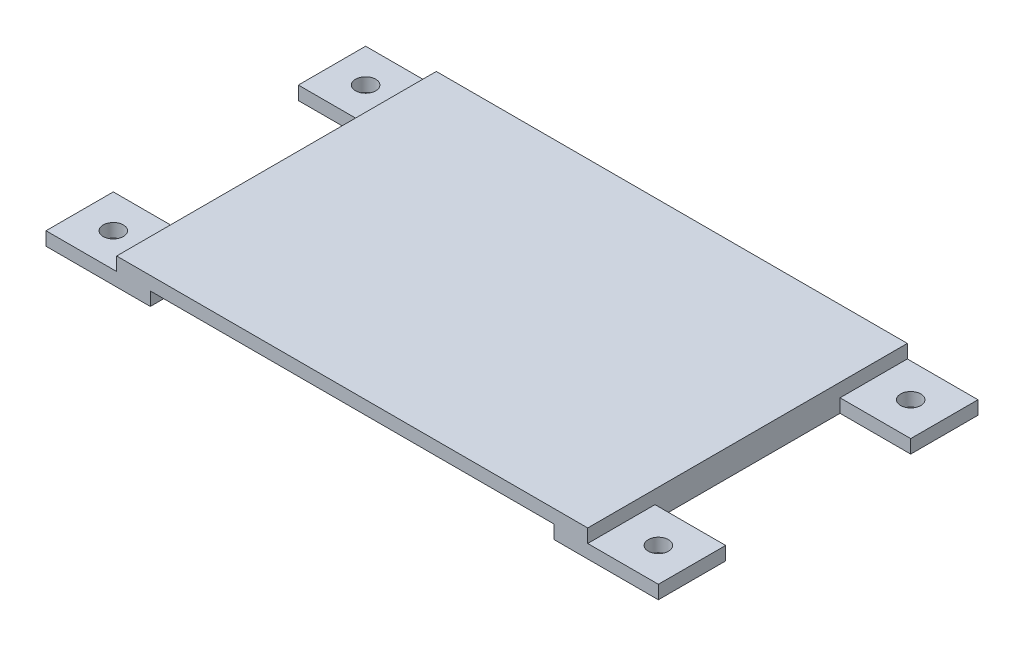
SolidWorks part; units mm, degrees
ref_plane "Front Plane" through (0, 0, 0) normal (0, 0, 1) x (1, 0, 0)
ref_plane "Top Plane" through (0, 0, 0) normal (0, 1, 0) x (1, 0, 0)
ref_plane "Right Plane" through (0, 0, 0) normal (1, 0, 0) x (0, 0, -1)
sketch "Sketch1" plane through (0, 0, 0) normal (0, 1, 0) x (1, 0, 0)
  line L0 (0, 0) -> (21, 0)
  line L1 (21, 0) -> (161, 0)
  line L8 (182, -95) -> (0, -95)
  line L9 (0, -95) -> (0, -75)
  line L10 (0, -75) -> (21, -75)
  line L11 (21, -75) -> (21, -20)
  line L12 (21, -20) -> (0, -20)
  line L13 (0, -20) -> (0, 0)
  line L14 (91, 0) -> (91, -95) construction
  line L15 (182, 0) -> (161, 0)
  line L16 (182, -20) -> (182, 0)
  line L17 (161, -20) -> (182, -20)
  line L18 (161, -75) -> (161, -20)
  line L19 (182, -75) -> (161, -75)
  line L20 (182, -95) -> (182, -75)
  circle A0 centre (10, -10) radius 3
  circle A1 centre (10, -85) radius 3
  circle A2 centre (172, -10) radius 3
  circle A3 centre (172, -85) radius 3
  dimension "D3" = 6
  dimension "D4" = 10
  dimension "D5" = 10
  dimension "D7" = 75
  dimension "D9" = 6
  dimension "D10" = 10
  dimension "D12" = 10
  dimension "D1" = 20
  dimension "D2" = 55
  dimension "D6" = 21
  dimension "D8" = 20
  dimension "D11" = 21
  dimension "D14" = 70
extrude "Boss-Extrude1" add sketch "Sketch1" along normal blind 8
sketch "Sketch2" plane through (0, 8, 0) normal (0, 1, 0) x (1, 0, 0)
  line L0 (182, 0) -> (0, 0) construction
  line L1 (0, -95) -> (21, -95)
  line L2 (0, -95) -> (0, -75)
  line L3 (0, -75) -> (21, -75)
  line L4 (21, -95) -> (21, -75)
  line L5 (0, -20) -> (21, -20)
  line L6 (0, -20) -> (0, 0)
  line L7 (0, 0) -> (21, 0)
  line L8 (21, -20) -> (21, 0)
  line L10 (182, -95) -> (161, -95)
  line L11 (182, -95) -> (182, -75)
  line L12 (182, -75) -> (161, -75)
  line L13 (161, -95) -> (161, -75)
  line L14 (182, 0) -> (161, 0)
  line L15 (182, 0) -> (182, -20)
  line L16 (182, -20) -> (161, -20)
  line L17 (161, 0) -> (161, -20)
extrude "Cut-Extrude1" cut sketch "Sketch2" against normal blind 4
sketch "Sketch3" plane through (0, 0, 0) normal (0, -1, 0) x (1, 0, 0)
  line L0 (0, 95) -> (182, 95) construction
  line L1 (31, 95) -> (151, 95)
  line L2 (31, 95) -> (31, 0)
  line L3 (31, 0) -> (151, 0)
  line L4 (151, 95) -> (151, 0)
  line L5 (182, 0) -> (0, 0) construction
  line L6 (21, 20) -> (21, 75) construction
  line L7 (161, 75) -> (161, 20) construction
  dimension "D1" = 10
  dimension "D2" = 10
extrude "Cut-Extrude2" cut sketch "Sketch3" against normal blind 4
